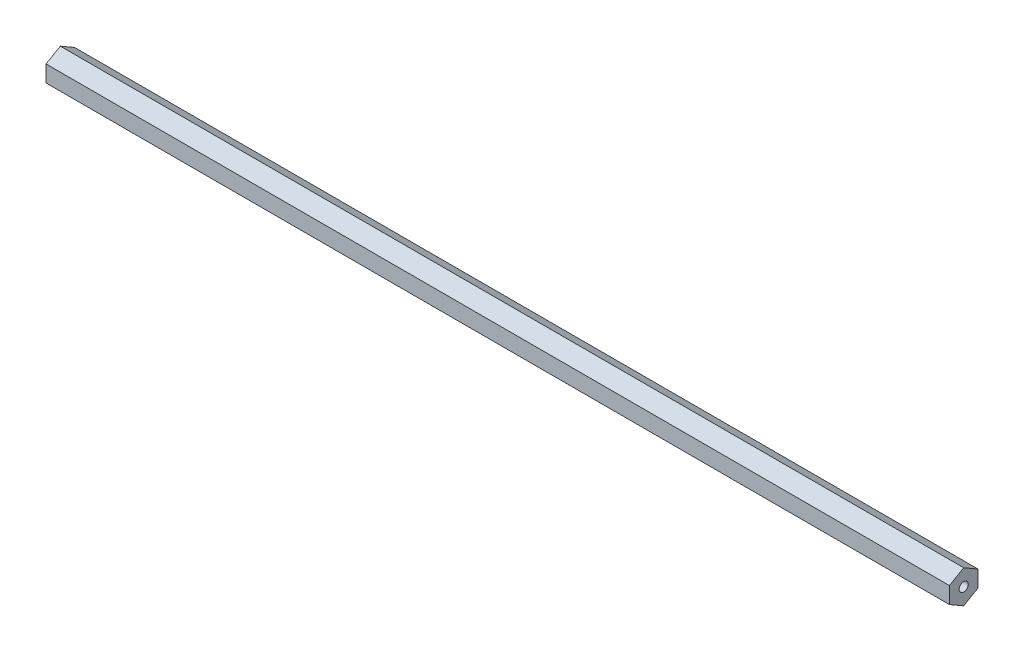
SolidWorks part; units mm, degrees
material "7075-T6 (SN)"
ref_plane "Front Plane" through (0, 0, 0) normal (0, 0, 1) x (1, 0, 0)
ref_plane "Top Plane" through (0, 0, 0) normal (0, 1, 0) x (1, 0, 0)
ref_plane "Right Plane" through (0, 0, 0) normal (1, 0, 0) x (0, 0, -1)
sketch "Sketch1" plane through (0, 0, 0) normal (1, 0, 0) x (0, 0, -1)
  line L1 (0, 7.3323) -> (-6.35, 3.6662)
  line L2 (-6.35, 3.6662) -> (-6.35, -3.6662)
  line L3 (-6.35, -3.6662) -> (0, -7.3323)
  line L4 (0, -7.3323) -> (6.35, -3.6662)
  line L5 (6.35, -3.6662) -> (6.35, 3.6662)
  line L6 (6.35, 3.6662) -> (0, 7.3323)
  circle A2 centre (0, 0) radius 6.35 construction
  dimension "D2" = 12.7
extrude "Boss-Extrude1" add sketch "Sketch1" along normal mid plane 401.6375
sketch "Sketch3" plane through (-200.8187, 0, 0) normal (-1, 0, 0) x (0, 0, 1)
  circle A0 centre (0, 0) radius 6.35
  dimension "D1" = 12.7
hole_wizard "#10-32 Tapped Hole1" positions "3DSketch1" profile "Sketch4" tap size "#10-32" standard "ANSI Inch"
sketch3d "3DSketch1"
  point P9 (200.8187, 0, 0)
  point P27 (-200.8187, 0, 0)
  point P30 (0, 0, 0)
sketch "Sketch4" plane through (200.8187, 0, 0) normal (0, 1, 0) x (0, 0, -1)
  line L0 (0, 0) -> (0, 17.5608)
  line L1 (0, 17.5608) -> (2.0193, 16.3474)
  line L2 (2.0193, 16.3474) -> (2.0193, 0)
  line L5 (2.0193, 0) -> (0, 0)
  line L10 (0, 17.5608) -> (-2.0193, 16.3474) construction
  line L11 (0, -6.35) -> (0, 107.95) construction
  dimension "Tap Drill Dia." = 4.0386
  dimension "Tap Drill Depth" = 16.3474
  dimension "Drill Angle" = 118
cosmetic thread "Hole Thread2" parameters "D1"=13.97, "D2"=4.826
cosmetic thread "Hole Thread3" parameters "D1"=13.97, "D2"=4.826
